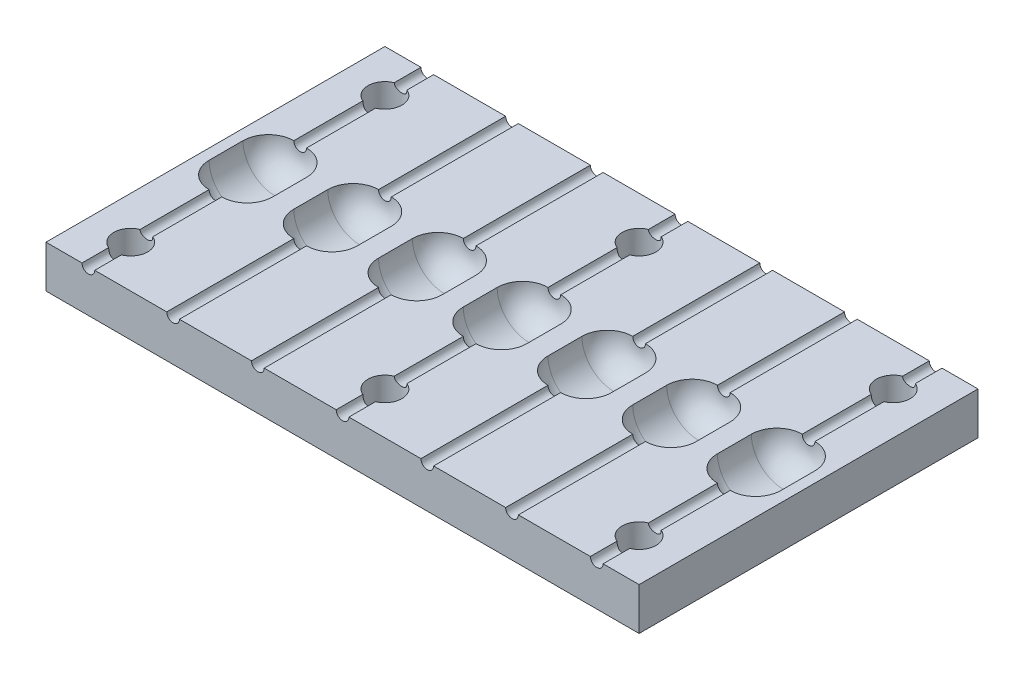
SolidWorks part; units mm, degrees
ref_plane "Plan de face" through (0, 0, 0) normal (0, 0, 1) x (1, 0, 0)
ref_plane "Plan de dessus" through (0, 0, 0) normal (0, 1, 0) x (1, 0, 0)
ref_plane "Plan de droite" through (0, 0, 0) normal (1, 0, 0) x (0, 0, -1)
sketch "Esquisse1" plane through (0, 0, 0) normal (0, 1, 0) x (1, 0, 0)
  line L1 (-50, 20) -> (20, 20)
  line L2 (-50, 20) -> (-50, -20)
  line L3 (-50, -20) -> (20, -20)
  line L4 (20, 20) -> (20, -20)
  dimension "D1" = 70
  dimension "D2" = 40
  dimension "D3" = 20
extrude "Boss.-Extru.1" add sketch "Esquisse1" along normal blind 5 contours L1 L4 L3 L2
sketch "Esquisse2" plane through (0, 0, 0) normal (0, 0, 1) x (1, 0, 0)
  line L0 (-38.75, 5) -> (-31.25, 5)
  line L1 (-50, 5) -> (-50, 0) construction
  line L3 (-48.75, 5) -> (-41.25, 5)
  line L4 (-28.75, 5) -> (-21.25, 5)
  line L5 (-18.75, 5) -> (-11.25, 5)
  line L6 (-8.75, 5) -> (-1.25, 5)
  line L7 (1.25, 5) -> (8.75, 5)
  line L8 (11.25, 5) -> (18.75, 5)
  line L11 (-50, 5) -> (20, 5) construction
  line L12 (21.25, 5) -> (28.75, 5) [skipped]
  line L13 (31.25, 5) -> (38.75, 5) [skipped]
  arc A0 (-48.75, 5) -> (-41.25, 5) centre (-45, 5) ccw
  arc A1 (-38.75, 5) -> (-31.25, 5) centre (-35, 5) ccw
  arc A2 (-28.75, 5) -> (-21.25, 5) centre (-25, 5) ccw
  arc A3 (-18.75, 5) -> (-11.25, 5) centre (-15, 5) ccw
  arc A4 (-8.75, 5) -> (-1.25, 5) centre (-5, 5) ccw
  arc A5 (1.25, 5) -> (8.75, 5) centre (5, 5) ccw
  arc A6 (11.25, 5) -> (18.75, 5) centre (15, 5) ccw
  arc A9 (21.25, 5) -> (28.75, 5) centre (25, 5) ccw [skipped]
  arc A10 (31.25, 5) -> (38.75, 5) centre (35, 5) ccw [skipped]
  dimension "D2" = 7.5
  dimension "D1" = 9
  dimension "D3" = 5
extrude "Enlèv. mat.-Extru.1" cut sketch "Esquisse2" against normal blind 5 and the other way blind 5
sketch "Esquisse4" plane through (0, 5, 0) normal (0, 1, 0) x (1, 0, 0)
  line L0 (-50, 20) -> (-50, -20) construction
  line L1 (-50, 20) -> (20, 20) construction
  line L2 (20, 20) -> (20, -20) construction
  line L3 (-50, -20) -> (20, -20) construction
  circle A0 centre (-45, -15) radius 2
  circle A1 centre (-45, 15) radius 2
  circle A2 centre (15, 15) radius 2
  circle A3 centre (15, -15) radius 2
  circle A4 centre (-15, 15) radius 2
  circle A5 centre (-15, -15) radius 2
  dimension "D1" = 4
  dimension "D2" = 5
  dimension "D3" = 5
  dimension "D4" = 5
  dimension "D5" = 5
  dimension "D6" = 35
extrude "Enlèv. mat.-Extru.3" cut sketch "Esquisse4" against normal up to next
fillet "Congé1" radius 3 14 edges at (-45, 1.25, 5) (-35, 1.25, 5) (-25, 1.25, 5) (-15, 1.25, 5) (-5, 1.25, 5) (15, 1.25, 5) (5, 1.25, 5) (15, 1.25, -5) (5, 1.25, -5) (-5, 1.25, -5) (-15, 1.25, -5) (-25, 1.25, -5) (-35, 1.25, -5) (-45, 1.25, -5)
sketch "Esquisse5" plane through (0, 5, 0) normal (0, 1, 0) x (1, 0, 0)
  line L0 (-45, 27.0634) -> (-45, -26.9933) construction
  line L1 (-50, 20) -> (20, 20) construction
  line L2 (-45, 20) -> (-45.75, 20)
  line L3 (-45, 20) -> (-45, -20)
  line L4 (-45, -20) -> (-45.75, -20)
  line L5 (-45.75, 20) -> (-45.75, -20)
  line L6 (-50, -20) -> (20, -20) construction
revolve "Enlèvement de matière-Révolution1" cut sketch "Esquisse5" angle 360 about L0
pattern_linear "Répétition linéaire1" count 7 spacing 10 along (1, 0, 0) of "Enlèvement de matière-Révolution1"
